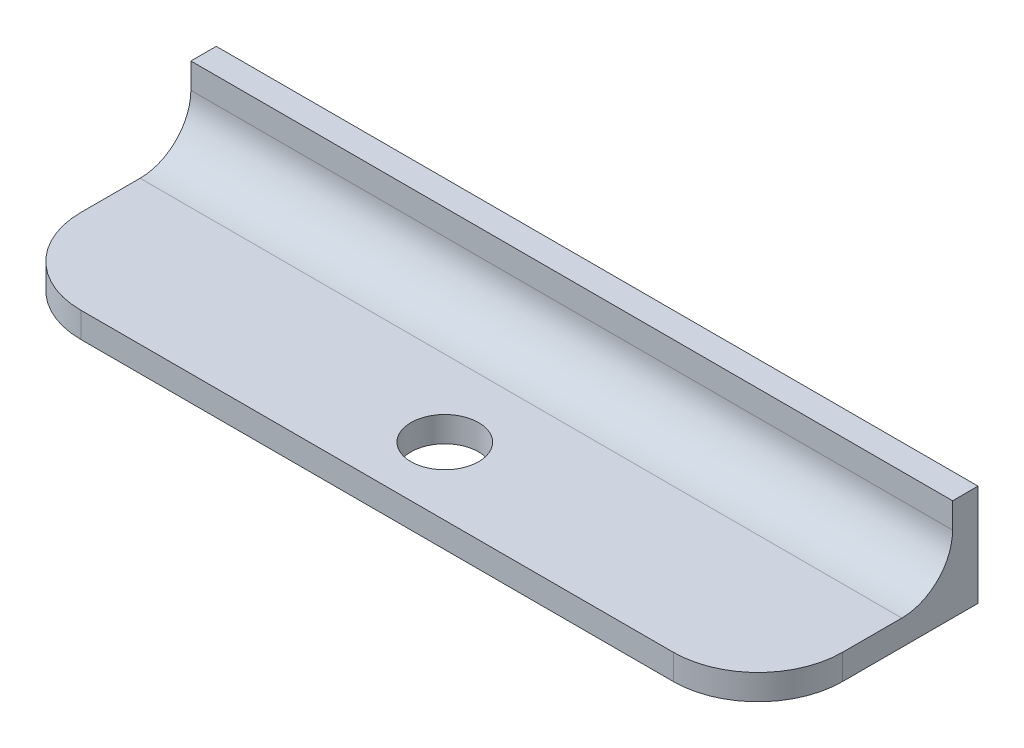
SolidWorks part; units mm, degrees
ref_plane "Front Plane" through (0, 0, 0) normal (0, 0, 1) x (1, 0, 0)
ref_plane "Top Plane" through (0, 0, 0) normal (0, 1, 0) x (1, 0, 0)
ref_plane "Right Plane" through (0, 0, 0) normal (1, 0, 0) x (0, 0, -1)
sketch "Sketch1" plane through (0, 0, 0) normal (0, 1, 0) x (1, 0, 0)
  line L0 (0, 0) -> (0, 9) construction
  line L2 (-22.5, 9) -> (22.5, 9)
  line L3 (-22.5, 9) -> (-22.5, 1)
  line L4 (-17.5, -4) -> (17.5, -4)
  line L5 (22.5, 9) -> (22.5, 1)
  circle A0 centre (0, 0) radius 2
  arc A1 (17.5, -4) -> (22.5, 1) centre (17.5, 1) ccw
  arc A2 (-22.5, 1) -> (-17.5, -4) centre (-17.5, 1) ccw
  point P10 (22.5, -4)
  point P13 (-22.5, -4)
  dimension "D1" = 4
  dimension "D2" = 9
  dimension "D5" = 5
  dimension "D3" = 4
  dimension "D4" = 45
extrude "Boss-Extrude1" add sketch "Sketch1" along normal blind 1.5
sketch "Sketch2" plane through (0, 1.5, 0) normal (0, 1, 0) x (1, 0, 0)
  line L1 (22.5, 1) -> (22.5, 9) construction
  line L2 (-22.5, 9) -> (22.5, 9)
  line L3 (-22.5, 9) -> (-22.5, 7.5)
  line L4 (-22.5, 7.5) -> (22.5, 7.5)
  line L6 (22.5, 9) -> (22.5, 7.5)
  dimension "D1" = 1.5
extrude "Boss-Extrude2" add sketch "Sketch2" along normal blind 4.5
fillet "Fillet1" radius 3 1 edges
